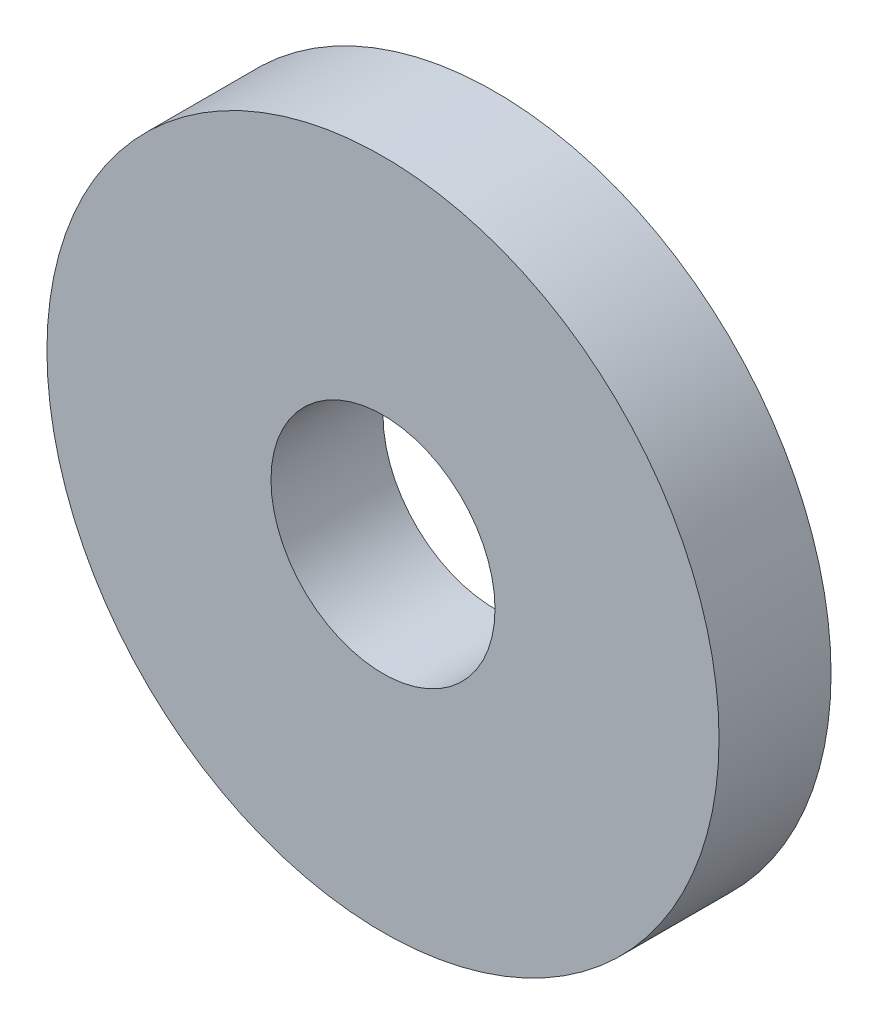
SolidWorks part; units mm, degrees
ref_plane "Alzado" through (0, 0, 0) normal (0, 0, 1) x (1, 0, 0)
ref_plane "Planta" through (0, 0, 0) normal (0, 1, 0) x (1, 0, 0)
ref_plane "Vista lateral" through (0, 0, 0) normal (1, 0, 0) x (0, 0, -1)
sketch "Croquis1" plane through (0, 0, 0) normal (0, 0, 1) x (1, 0, 0)
  circle A0 centre (0, 0) radius 7.5
  circle A1 centre (0, 0) radius 2.5
  point P5 (0, 0)
  dimension "D1" = 15
  dimension "D2" = 5
extrude "Saliente-Extruir1" add sketch "Croquis1" along normal blind 2.5
